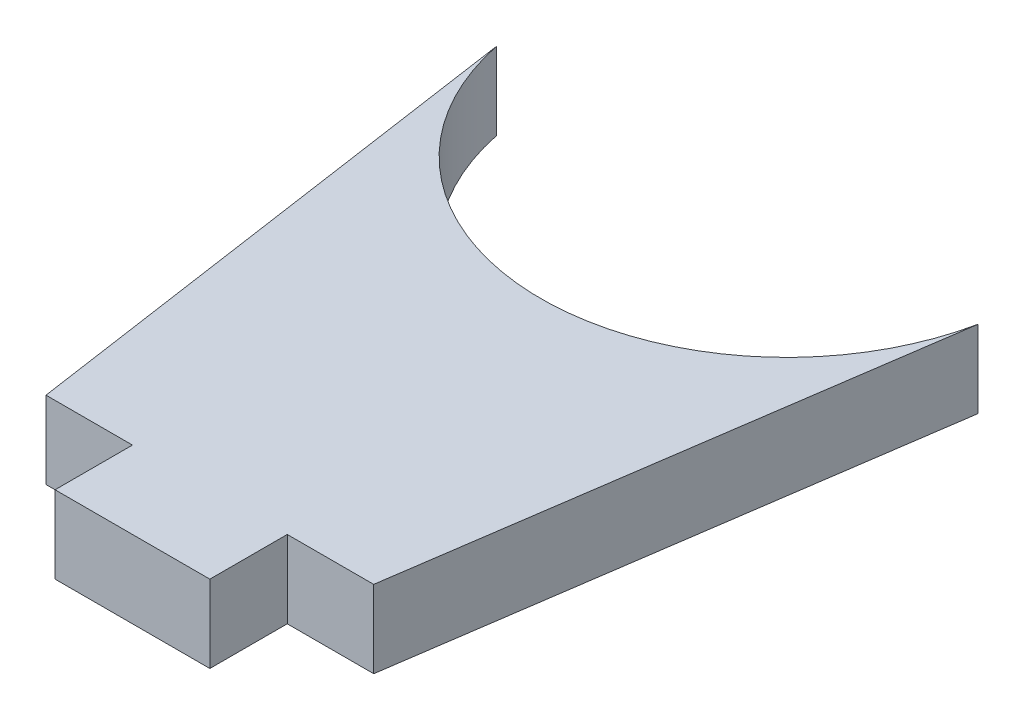
SolidWorks part; units mm, degrees
ref_plane "Front Plane" through (0, 0, 0) normal (1, 0, 0) x (0, 1, 0)
ref_plane "Top Plane" through (0, 0, 0) normal (0, 0, 1) x (0, 1, 0)
ref_plane "Right Plane" through (0, 0, 0) normal (0, 1, 0) x (-1, 0, 0)
sketch "Sketch1" plane through (0, 0, 0) normal (0, 1, 0) x (-1, 0, 0)
  line L0 (0, 0) -> (0, 50000) construction
  line L1 (0, 0) -> (15.875, 0) construction
  line L2 (0, 0) -> (15.8146, 1.3836) construction
  line L6 (-10.5846, 37.2586) -> (-5, 37.2586)
  line L7 (-5, 37.2586) -> (5, 37.2586) construction
  line L8 (-5, 37.2586) -> (-5, 42.2586)
  line L9 (5, 37.2586) -> (5, 42.2586)
  line L10 (5, 42.2586) -> (-5, 42.2586)
  line L11 (5, 37.2586) -> (10.5846, 37.2586)
  line L12 (10.5846, 37.2586) -> (15.8146, 1.3836)
  line L13 (-10.5846, 37.2586) -> (-15.8146, 1.3836)
  arc A0 (15.8146, 1.3836) -> (-15.8146, 1.3836) centre (0, 0) ccw
  point P12 (2.5, 37.2586)
  dimension "D1" = 31.75
  dimension "D2" = 5
  dimension "D4" = 15.875
  dimension "D5" = 10
  dimension "D6" = 5
extrude "Boss-Extrude1" add sketch "Sketch1" along normal mid plane 5 contours A0 L12 L11 L9 L10 L8 L6 L13
